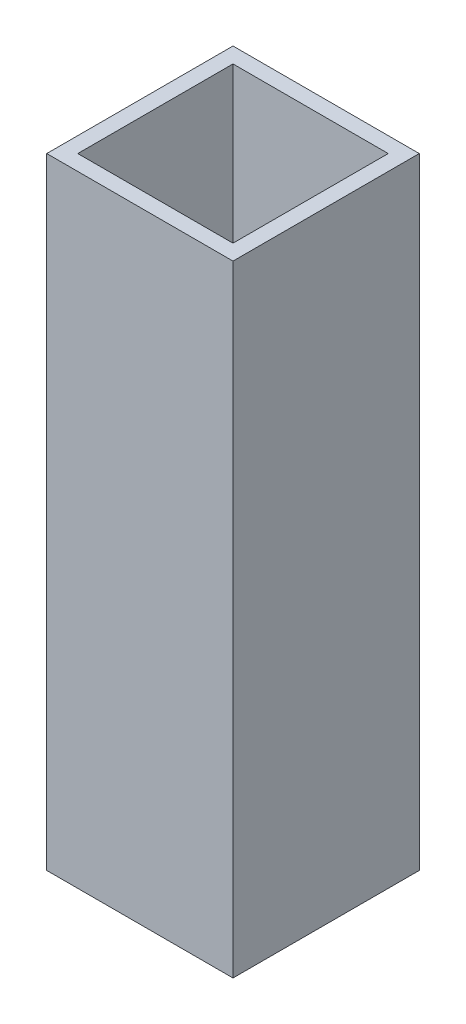
SolidWorks part; units mm, degrees
ref_plane "Front Plane" through (0, 0, 0) normal (0, 0, 1) x (1, 0, 0)
ref_plane "Top Plane" through (0, 0, 0) normal (0, 1, 0) x (1, 0, 0)
ref_plane "Right Plane" through (0, 0, 0) normal (1, 0, 0) x (0, 0, -1)
other "Configuration Table"
sketch "Sketch1" plane through (0, 0, 0) normal (0, 1, 0) x (1, 0, 0)
  line L1 (8, -6) -> (20, -6)
  line L2 (8, -6) -> (8, 6)
  line L3 (8, 6) -> (20, 6)
  line L4 (20, -6) -> (20, 6)
  line L5 (8, -6) -> (20, 6) construction
  line L6 (8, 6) -> (20, -6) construction
  point P5 (14, 0)
  dimension "D1" = 12
  dimension "D2" = 12
extrude "Channel" add sketch "Sketch1" along normal blind 40 from offset 63.5
sketch "Sketch2" plane through (0, 0, 0) normal (0, 1, 0) x (1, 0, 0)
  line L1 (9, -5) -> (19, -5)
  line L2 (9, -5) -> (9, 5)
  line L3 (9, 5) -> (19, 5)
  line L4 (19, -5) -> (19, 5)
  line L5 (9, -5) -> (19, 5) construction
  line L6 (9, 5) -> (19, -5) construction
  point P5 (14, 0)
  dimension "D1" = 10
  dimension "D2" = 10
extrude "Light_Path_10mm" cut sketch "Sketch2" along normal through all and the other way through all
equation "\"Jar_OD\"= 90  'ASSUMED - Part G fallback - jar outer diameter"
equation "\"Jar_H\"= 120  'ASSUMED - Part G fallback - jar height"
equation "\"Pump_L\"= 45  'ASSUMED - Part G fallback"
equation "\"Pump_W\"= 24  'ASSUMED - Part G fallback"
equation "\"Pump_H\"= 33  'ASSUMED - Part G fallback"
equation "\"Pump_Outlet_OD\"= 7.5  'ASSUMED - Part G fallback"
equation "\"Tube_OD\"= 8  'ASSUMED - Part G fallback"
equation "\"Tube_ID\"= 6  'ASSUMED - Part G fallback"
equation "\"TDS_Body_Dia\"= 12  'ASSUMED - Part G fallback"
equation "\"TDS_Wet_Len\"= 45  'ASSUMED - Part G fallback - length in water"
equation "\"DS_Tube_Dia\"= 6  'ASSUMED - Part G fallback"
equation "\"DS_Tube_Len\"= 50  'ASSUMED - Part G fallback"
equation "\"ORP_Body_Dia\"= 12  'ASSUMED - Part G fallback"
equation "\"ORP_Body_Len\"= 150  'ASSUMED - Part G fallback"
equation "\"ORP_Cap_Dia\"= 16  'ASSUMED - Part G fallback"
equation "\"Turb_W\"= 33  'ASSUMED - Part G fallback - head width"
equation "\"Turb_D\"= 28  'ASSUMED - Part G fallback - head depth"
equation "\"Turb_H\"= 30  'ASSUMED - Part G fallback - head height"
equation "\"Turb_Slot_W\"= 10  'ASSUMED - Part G fallback - slot width"
equation "\"Flow_L\"= 62  'ASSUMED - Part G fallback YF-S201"
equation "\"Flow_W\"= 36  'ASSUMED - Part G fallback"
equation "\"Flow_H\"= 35  'ASSUMED - Part G fallback"
equation "\"Thread_G12_OD\"= 20.955  'ASSUMED - Part G fallback thread G1/2 (major diameter)"
equation "\"Valve_L\"= 75  'ASSUMED - Part G fallback"
equation "\"Valve_W\"= 45  'ASSUMED - Part G fallback"
equation "\"Valve_H\"= 60  'ASSUMED - Part G fallback"
equation "\"Tee_L\"= 40  'ASSUMED - Part G fallback - overall length"
equation "\"Tee_Branch_L\"= 25  'ASSUMED - Part G fallback"
equation "\"Tee_OD\"= 12  'ASSUMED - Part G fallback"
equation "\"LED_Board_L\"= 20  'ASSUMED - Part G fallback"
equation "\"LED_Board_W\"= 20  'ASSUMED - Part G fallback - LED at centre"
equation "\"GUVA_L\"= 20  'ASSUMED - Part G fallback"
equation "\"GUVA_W\"= 12  'ASSUMED - Part G fallback - sensor at centre"
equation "\"Reed_L\"= 27  'ASSUMED - Part G fallback MC-38 half"
equation "\"Reed_W\"= 14  'ASSUMED - Part G fallback"
equation "\"Reed_H\"= 8  'ASSUMED - Part G fallback"
equation "\"ESP_L\"= 51  'ASSUMED - Part G fallback"
equation "\"ESP_W\"= 28  'ASSUMED - Part G fallback"
equation "\"TFT_L\"= 58  'ASSUMED - Part G fallback - board"
equation "\"TFT_W\"= 35  'ASSUMED - Part G fallback - board"
equation "\"TFT_Win_L\"= 35  'ASSUMED - Part G fallback - visible window"
equation "\"TFT_Win_W\"= 28  'ASSUMED - Part G fallback - visible window"
equation "\"Relay_L\"= 50  'ASSUMED - Part G fallback"
equation "\"Relay_W\"= 26  'ASSUMED - Part G fallback"
equation "\"Relay_H\"= 19  'ASSUMED - Part G fallback"
equation "\"Mosfet_L\"= 34  'ASSUMED - Part G fallback"
equation "\"Mosfet_W\"= 17  'ASSUMED - Part G fallback"
equation "\"Mosfet_H\"= 12  'ASSUMED - Part G fallback"
equation "\"TDS_Board_L\"= 42  'ASSUMED - Part G fallback"
equation "\"TDS_Board_W\"= 32  'ASSUMED - Part G fallback"
equation "\"Turb_Board_L\"= 38  'ASSUMED - Part G fallback"
equation "\"Turb_Board_W\"= 28  'ASSUMED - Part G fallback"
equation "\"BNC_Thread_Dia\"= 9.5  'ASSUMED - Part G fallback"
equation "\"Plate_L\"= 420  'ASSUMED - Part G fallback"
equation "\"Plate_W\"= 297  'ASSUMED - Part G fallback"
equation "\"Plate_T\"= 6  'ASSUMED - Part G fallback"
equation "\"Booster_L\"= 150  'ASSUMED - Part G fallback - booster pump"
equation "\"Booster_W\"= 95  'ASSUMED - Part G fallback"
equation "\"Booster_H\"= 100  'ASSUMED - Part G fallback"
equation "\"PTube_OD\"= 6.35  'ASSUMED - Part G fallback - product tube 1/4 inch"
equation "\"Qz_Out\"= 12  'ASSUMED - Part G fallback - quartz channel outside square"
equation "\"Qz_Path\"= 10  'ASSUMED - Part G fallback - quartz channel inside light path"
equation "\"Qz_L\"= 40  'ASSUMED - Part G fallback - quartz channel length"
equation "\"LED860_Dia\"= 5  'ASSUMED - Part G fallback - 860 nm LED"
equation "\"BPW_L\"= 5.4  'ASSUMED - Part G fallback - BPW34"
equation "\"BPW_W\"= 4.3  'ASSUMED - Part G fallback - BPW34"
equation "\"Cart_Dia\"= 50  'ASSUMED - Part G fallback - sediment and pre-carbon cartridges"
equation "\"Cart_L\"= 255  'ASSUMED - Part G fallback"
equation "\"UF_Dia\"= 50  'ASSUMED - Part G fallback - UF cartridge"
equation "\"UF_L\"= 260  'ASSUMED - Part G fallback"
equation "\"RO_Dia\"= 62  'ASSUMED - Part G fallback - RO membrane housing"
equation "\"RO_L\"= 300  'ASSUMED - Part G fallback"
equation "\"UVC_Dia\"= 40  'ASSUMED - Part G fallback - UV-C chamber"
equation "\"UVC_L\"= 300  'ASSUMED - Part G fallback"
equation "\"Tank_W\"= 260  'ASSUMED - Part G fallback - storage tank"
equation "\"Tank_D\"= 160  'ASSUMED - Part G fallback"
equation "\"Tank_H\"= 300  'ASSUMED - Part G fallback"
equation "\"Cab_W\"= 400  'ASSUMED - Part G fallback - purifier cabinet"
equation "\"Cab_D\"= 270  'ASSUMED - Part G fallback"
equation "\"Cab_H\"= 560  'ASSUMED - Part G fallback"
equation "\"ORP_Board_L\"= 40  'ASSUMED - Part G fallback - ORP buffer board"
equation "\"ORP_Board_W\"= 30  'ASSUMED - Part G fallback"
equation "\"Opt_Board_L\"= 50  'ASSUMED - Part G fallback - optical front-end board"
equation "\"Opt_Board_W\"= 40  'ASSUMED - Part G fallback"
equation "\"Buck_L\"= 43  'ASSUMED - Part G fallback - 12 V to 5 V buck module"
equation "\"Buck_W\"= 21  'ASSUMED - Part G fallback"
equation "\"Buck_H\"= 14  'ASSUMED - Part G fallback"
equation "\"BB_L\"= 165  'ASSUMED - Part G fallback - breadboard (As_Built_R3 only)"
equation "\"BB_W\"= 55  'ASSUMED - Part G fallback"
equation "\"BB_H\"= 10  'ASSUMED - Part G fallback"
equation "\"Cuv_W\"= 12.5  'ASSUMED - old R3 cuvette (station suppressed in SS4)"
equation "\"Cuv_D\"= 12.5  'ASSUMED - old R3 cuvette (station suppressed in SS4)"
equation "\"Cuv_H\"= 45  'ASSUMED - old R3 cuvette (station suppressed in SS4)"
equation "\"Probe_Clr\"= 0.3  'DESIGN VALUE - Part C rule 3 - printed probe hole = diameter + 0.3"
equation "\"Label_H\"= 0.6  'DESIGN VALUE - Part D - raised label height"
equation "\"D1@Sketch1\" = \"Qz_Out\""
equation "\"D2@Sketch1\" = \"Qz_Out\""
equation "\"D1@Channel\" = \"Qz_L\""
equation "\"D1@Sketch2\" = \"Qz_Path\""
equation "\"D2@Sketch2\" = \"Qz_Path\""
